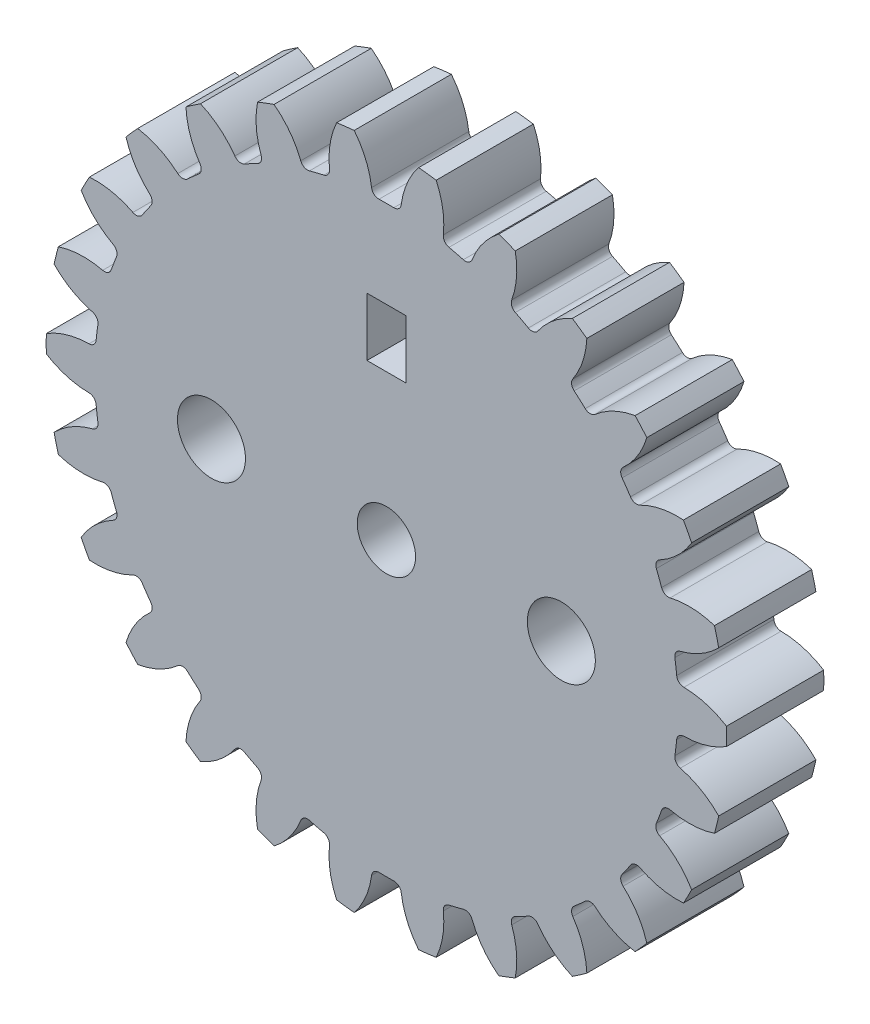
SolidWorks part; units mm, degrees
ref_plane "Front" through (0, 0, 0) normal (0, 0, 1) x (1, 0, 0)
ref_plane "Top" through (0, 0, 0) normal (0, 1, 0) x (1, 0, 0)
ref_plane "Right" through (0, 0, 0) normal (1, 0, 0) x (0, 0, -1)
sketch "Sketch1" plane through (0, 0, 0) normal (0, 0, 1) x (1, 0, 0)
  circle A0 centre (0, 0) radius 15
  circle A1 centre (0, 0) radius 17.5
  circle A2 centre (0, 0) radius 16.25
  dimension "D1" = 35
  dimension "D2" = 30
  dimension "D3" = 32.5
extrude "Boss-Extrude1" add sketch "Sketch1" along normal mid plane 5 contours A1
sketch "Sketch3" plane through (0, 0, 0) normal (0, 0, 1) x (1, 0, 0)
  line L0 (0, 0) -> (0, 17.5) construction
  line L1 (0, 0) -> (-0.7315, 14.9822) construction
  line L2 (-0.9812, 16.2204) -> (0.9812, 16.2204) construction
  line L3 (-1.4257, 17.4418) -> (0, 13.5247) construction
  line L4 (0, 0) -> (2.1094, 17.3724) construction
  line L5 (0.9812, 16.2204) -> (2.9291, 15.9838) construction
  arc A0 (-0.7315, 14.9822) -> (0.7315, 14.9822) centre (0, 0) cw
  arc A4 (1.6577, 17.4213) -> (-1.6577, 17.4213) centre (0, 0) ccw
  circle A5 centre (0, 0) radius 17.5 construction
  arc A7 (-1.6577, 17.4213) -> (-0.7315, 14.9822) centre (-4.9488, 14.7762) cw
  arc A10 (1.6577, 17.4213) -> (0.7315, 14.9822) centre (4.9488, 14.7762) ccw
  circle A11 centre (0, 0) radius 15 construction
  circle A12 centre (0, 0) radius 16.25 construction
  dimension "D1" = 20
  dimension "D2" = 6.923
extrude "Cut-Extrude1" cut sketch "Sketch3" against normal through all both and the other way through all
fillet "Fillet2" radius 0.375 2 edges at (0.7315, 14.9822, 0) (-0.7315, 14.9822, 0)
pattern_circular "CirPattern1" count 26 over 360 about axis through (0, 0, 0) along (0, 0, 1) of "Cut-Extrude1", "Fillet2"
sketch "Sketch4" plane through (0, 0, 0) normal (0, 0, 1) x (1, 0, 0)
  circle A0 centre (0, 0) radius 1.5
  dimension "D1" = 3
extrude "String_Hole" cut sketch "Sketch4" against normal through all both and the other way through all
sketch "Sketch5" plane through (0, 0, 0) normal (0, 0, 1) x (1, 0, 0)
  line L0 (-9, 0) -> (9, 0) construction
  circle A0 centre (9, 0) radius 1.75
  circle A1 centre (-9, 0) radius 1.75
  dimension "D2" = 3.5
  dimension "D1" = 18
extrude "To_Knuckle_Mount" cut sketch "Sketch5" against normal through all both and the other way through all
sketch "Sketch6" plane through (0, 0, 2.5) normal (0, 0, 1) x (1, 0, 0)
  line L0 (0, 0) -> (0, 15) construction
  line L2 (1, 7.5) -> (-1, 7.5)
  line L3 (1, 7.5) -> (1, 10.5)
  line L4 (1, 10.5) -> (-1, 10.5)
  line L5 (-1, 7.5) -> (-1, 10.5)
  line L6 (1, 7.5) -> (-1, 10.5) construction
  line L7 (1, 10.5) -> (-1, 7.5) construction
  arc A2 (0.3805, 14.9952) -> (-0.3805, 14.9952) centre (0, 0) ccw construction
  point P6 (0, 9)
  dimension "D1" = 2
  dimension "D2" = 3
  dimension "D3" = 9
extrude "For_Alignment" cut sketch "Sketch6" against normal blind 2
equation "\"od\"= 35'outside diameter"
equation "\"n\"= 26'number of teeth"
equation "\"m\"= \"od\" / ( \"n\" + 2 )'module"
equation "\"p\"= \"m\" * pi'pitch"
equation "\"d\"= \"m\" * \"n\"'primitive diameter"
equation "\"da\"= \"d\" + 2 * \"m\"'head diamater"
equation "\"df\"= \"d\" - 2 * \"m\"'foot diameter"
equation "\"D1@Sketch1\"=\"od\""
equation "\"D2@Sketch1\"=\"df\""
equation "\"D3@Sketch1\"=\"d\""
equation "\"D2@Sketch3\"=180/\"n\""
equation "\"D1@Fillet2\"=.3*\"m\""
equation "\"D1@CirPattern1\"=\"n\""
